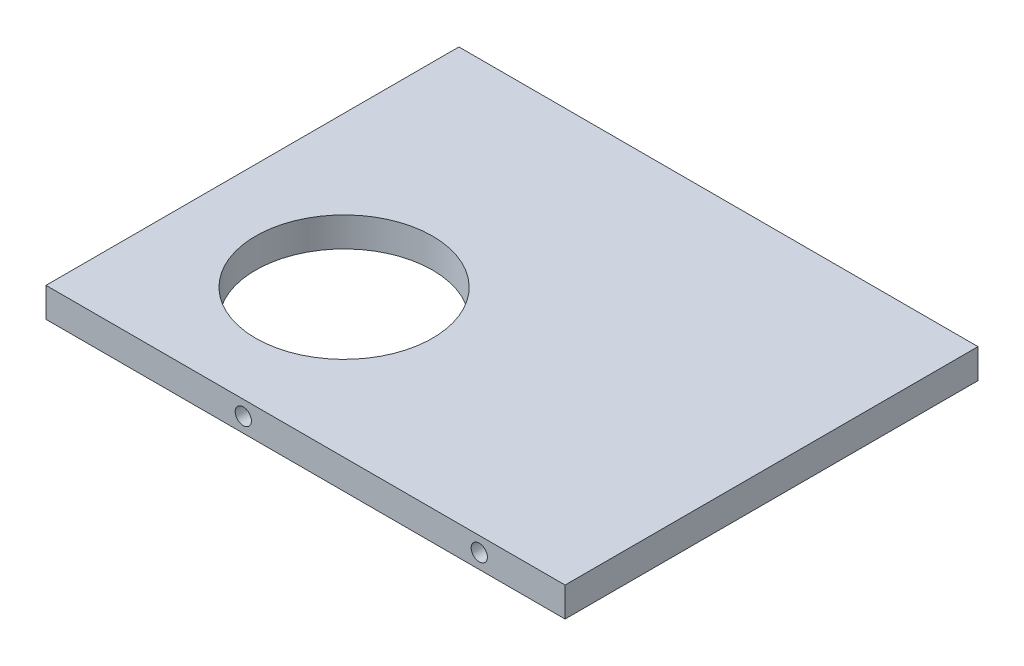
SolidWorks part; units mm, degrees
ref_plane "Front Plane" through (0, 0, 0) normal (0, 0, 1) x (1, 0, 0)
ref_plane "Top Plane" through (0, 0, 0) normal (0, 1, 0) x (1, 0, 0)
ref_plane "Right Plane" through (0, 0, 0) normal (1, 0, 0) x (0, 0, -1)
sketch "Sketch1" plane through (0, 0, 0) normal (0, 1, 0) x (1, 0, 0)
  line L1 (-44, 35) -> (44, 35)
  line L2 (-44, 35) -> (-44, -35)
  line L3 (-44, -35) -> (44, -35)
  line L4 (44, 35) -> (44, -35)
  line L5 (-44, 35) -> (44, -35) construction
  line L6 (-44, -35) -> (44, 35) construction
  point P0 (0, 0)
  dimension "D1" = 70
  dimension "D2" = 88
extrude "Boss-Extrude1" add sketch "Sketch1" along normal blind 5
sketch "Sketch2" plane through (0, 0, 35) normal (0, 0, 1) x (1, 0, 0)
  line L0 (-44, 5) -> (-44, 0) construction
  line L1 (-44, 5) -> (44, 5) construction
  line L2 (38.5, 0) -> (-38.5, 0) construction
  circle A0 centre (-10.55, 2.5) radius 1.375
  circle A1 centre (29.45, 2.5) radius 1.375
  dimension "D1" = 2.75
  dimension "D2" = 2.75
  dimension "D6" = 2.5
  dimension "D3" = 33.45
  dimension "D4" = 2.5
  dimension "D5" = 40
extrude "Cut-Extrude1" cut sketch "Sketch2" against normal blind 5
sketch "Sketch4" plane through (0, 0, -35) normal (0, 0, -1) x (-1, 0, 0)
  line L1 (38.5, 0) -> (-38.5, 0) construction
  line L2 (44, 5) -> (44, 0) construction
  circle A0 centre (-29.45, 2.5) radius 1.375
  circle A1 centre (10.55, 2.5) radius 1.375
  point P8 (44, 2.5)
  dimension "D1" = 2.75
  dimension "D2" = 2.75
  dimension "D3" = 33.45
  dimension "D4" = 2.5
  dimension "D6" = 2.5
  dimension "D5" = 40
extrude "Cut-Extrude2" cut sketch "Sketch4" against normal blind 5
sketch "Sketch5" plane through (0, 5, 0) normal (0, 1, 0) x (1, 0, 0)
  line L0 (-44, -35) -> (44, -35) construction
  circle A0 centre (-18.4697, -10) radius 15
  dimension "D1" = 30
  dimension "D2" = 25
extrude "Cut-Extrude3" cut sketch "Sketch5" against normal through all
